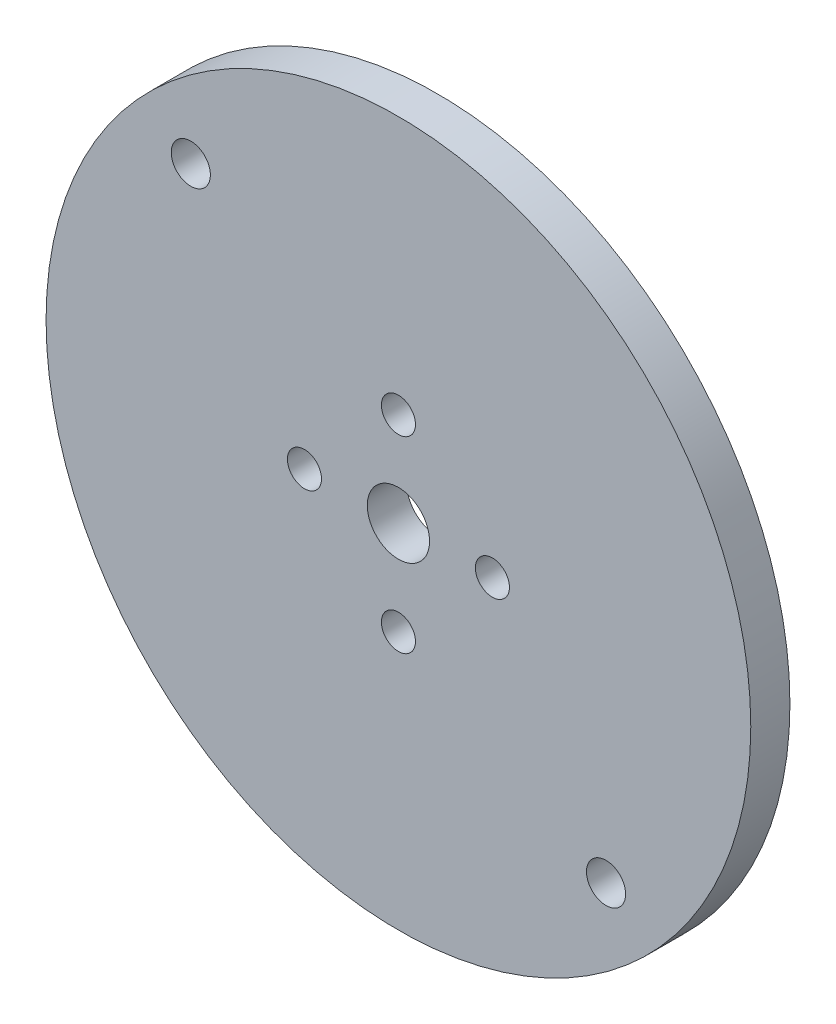
SolidWorks part; units mm, degrees
ref_plane "Front Plane" through (0, 0, 0) normal (0, 0, 1) x (1, 0, 0)
ref_plane "Top Plane" through (0, 0, 0) normal (0, 1, 0) x (1, 0, 0)
ref_plane "Right Plane" through (0, 0, 0) normal (1, 0, 0) x (0, 0, -1)
sketch "Sketch1" plane through (0, 0, 0) normal (0, 0, 1) x (1, 0, 0)
  circle A0 centre (0, 0) radius 45
  circle A2 centre (12, 0) radius 2.175
  circle A3 centre (0, 12) radius 2.175
  circle A4 centre (-12, 0) radius 2.175
  circle A5 centre (0, -12) radius 2.175
  circle A6 centre (0, 0) radius 3.975
  circle A10 centre (-26.5165, 26.5165) radius 2.5
  circle A11 centre (26.5165, -26.5165) radius 2.5
  dimension "D1" = 4.35
  dimension "D2" = 4.35
  dimension "D3" = 4.35
  dimension "D4" = 4.35
  dimension "D5" = 7.95
  dimension "D6" = 90
extrude "Boss-Extrude1" add sketch "Sketch1" along normal blind 5
